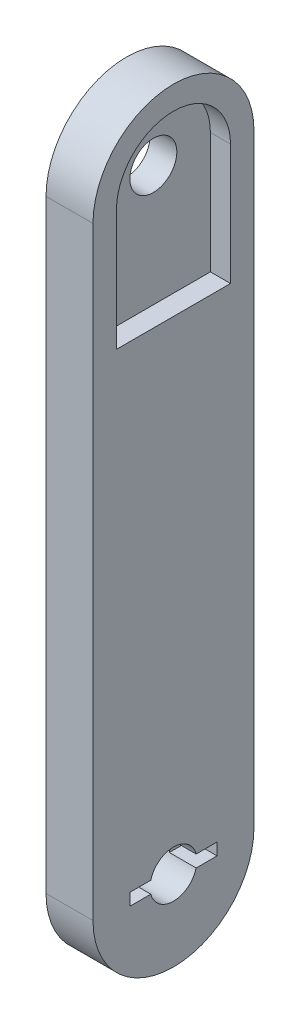
SolidWorks part; units mm, degrees
ref_plane "Front Plane" through (0, 0, 0) normal (0, 0, 1) x (1, 0, 0)
ref_plane "Top Plane" through (0, 0, 0) normal (0, 1, 0) x (1, 0, 0)
ref_plane "Right Plane" through (0, 0, 0) normal (1, 0, 0) x (0, 0, -1)
sketch "Sketch1" plane through (0, 0, 0) normal (1, 0, 0) x (0, 0, -1)
  line L0 (0, 45) -> (0, -45) construction
  line L1 (-25.5643, 0) -> (25.5643, 0) construction
  line L2 (-12, 45) -> (-12, -45)
  line L3 (12, 45) -> (12, -45)
  circle A0 centre (0, 45) radius 3.5
  circle A1 centre (0, -45) radius 3.5
  arc A2 (12, 45) -> (-12, 45) centre (0, 45) ccw
  arc A3 (-12, -45) -> (12, -45) centre (0, -45) ccw
  point P3 (0, 0)
  point P6 (0, 0)
  dimension "D1" = 7
  dimension "D2" = 24
  dimension "D3" = 7
  dimension "D4" = 24
  dimension "D5" = 90
extrude "Boss-Extrude1" add sketch "Sketch1" along normal blind 7
sketch "Sketch2" plane through (7, 0, 0) normal (1, 0, 0) x (0, 0, -1)
  line L0 (-8.5, 45) -> (-8.5, 27)
  line L1 (-8.5, 27) -> (8.5, 27)
  line L2 (8.5, 27) -> (8.5, 45)
  arc A0 (8.5, 45) -> (-8.5, 45) centre (0, 45) ccw
  dimension "D1" = 17
  dimension "D2" = 18
extrude "Cut-Extrude1" cut sketch "Sketch2" against normal blind 3
sketch "Sketch3" plane through (7, 0, 0) normal (1, 0, 0) x (0, 0, -1)
  line L0 (-6.5, -45.9) -> (6.5, -44.1) construction
  line L1 (-6.5, -44.1) -> (6.5, -44.1)
  line L2 (-6.5, -44.1) -> (-6.5, -45.9)
  line L3 (-6.5, -45.9) -> (6.5, -45.9)
  line L4 (6.5, -44.1) -> (6.5, -45.9)
  line L5 (0, -41.5) -> (0, -48.5) construction
  circle A0 centre (0, -45) radius 3.5 construction
  point P9 (0, -45)
  point P10 (0, -45)
  dimension "D1" = 13
  dimension "D2" = 1.8
extrude "Cut-Extrude2" cut sketch "Sketch3" against normal blind 4
